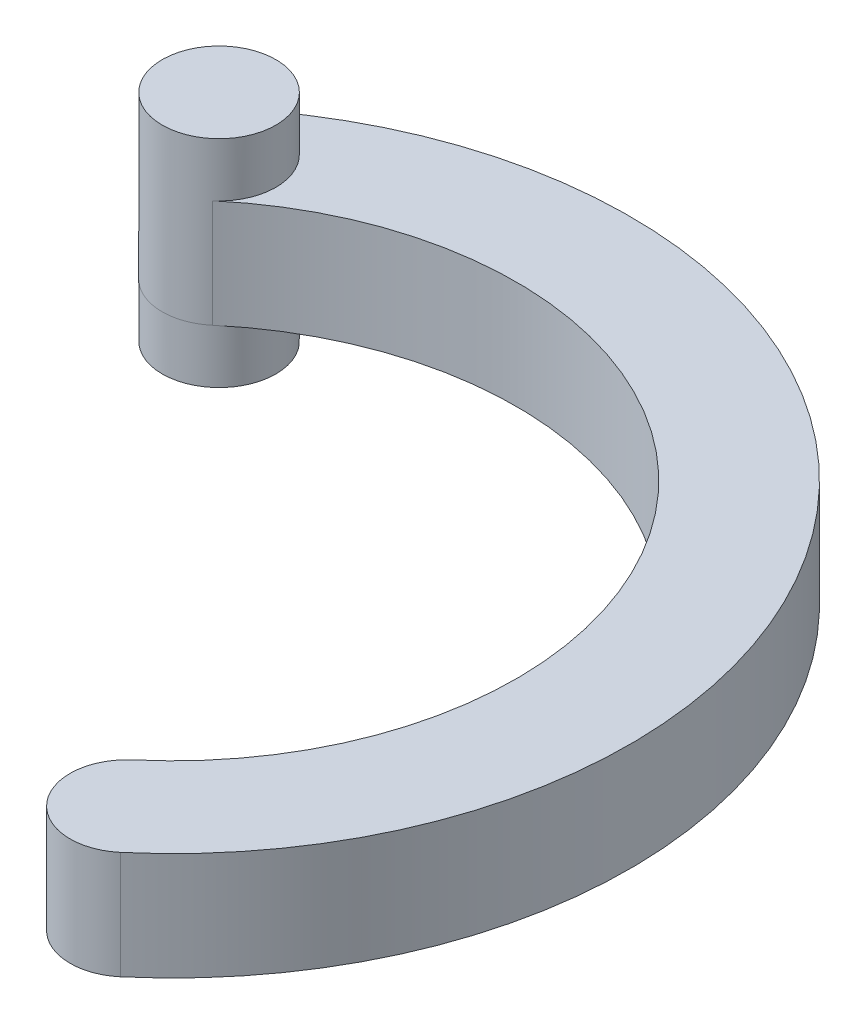
SolidWorks part; units mm, degrees
ref_plane "Front Plane" through (0, 0, 0) normal (0, 0, 1) x (1, 0, 0)
ref_plane "Top Plane" through (0, 0, 0) normal (0, 1, 0) x (1, 0, 0)
ref_plane "Right Plane" through (0, 0, 0) normal (1, 0, 0) x (0, 0, -1)
sketch "Sketch4" plane through (0, 0, 0) normal (0, 1, 0) x (1, 0, 0)
  arc A0 (0, 0) -> (48.0815, -56.632) centre (24.0407, -28.316) cw construction
  arc A1 (51.4932, -60.6505) -> (-3.4117, 4.0185) centre (24.0407, -28.316) ccw
  arc A2 (44.6697, -52.6136) -> (3.4117, -4.0185) centre (24.0407, -28.316) ccw
  arc A3 (44.6697, -52.6136) -> (51.4932, -60.6505) centre (48.0815, -56.632) ccw
  arc A4 (-3.4117, 4.0185) -> (3.4117, -4.0185) centre (0, 0) ccw
  point P3 (52.3568, -4.2753)
extrude "Boss-Extrude2" add sketch "Sketch4" along normal blind 10
sketch "Sketch5" plane through (0, 10, 0) normal (0, 1, 0) x (1, 0, 0)
  circle A0 centre (0, 0) radius 5.2714
extrude "Boss-Extrude3" add sketch "Sketch5" along normal blind 5
sketch "Sketch8" plane through (0, 0, 0) normal (0, -1, 0) x (1, 0, 0)
  circle A0 centre (0, 0) radius 5.27
extrude "Boss-Extrude4" add sketch "Sketch8" along normal blind 5
